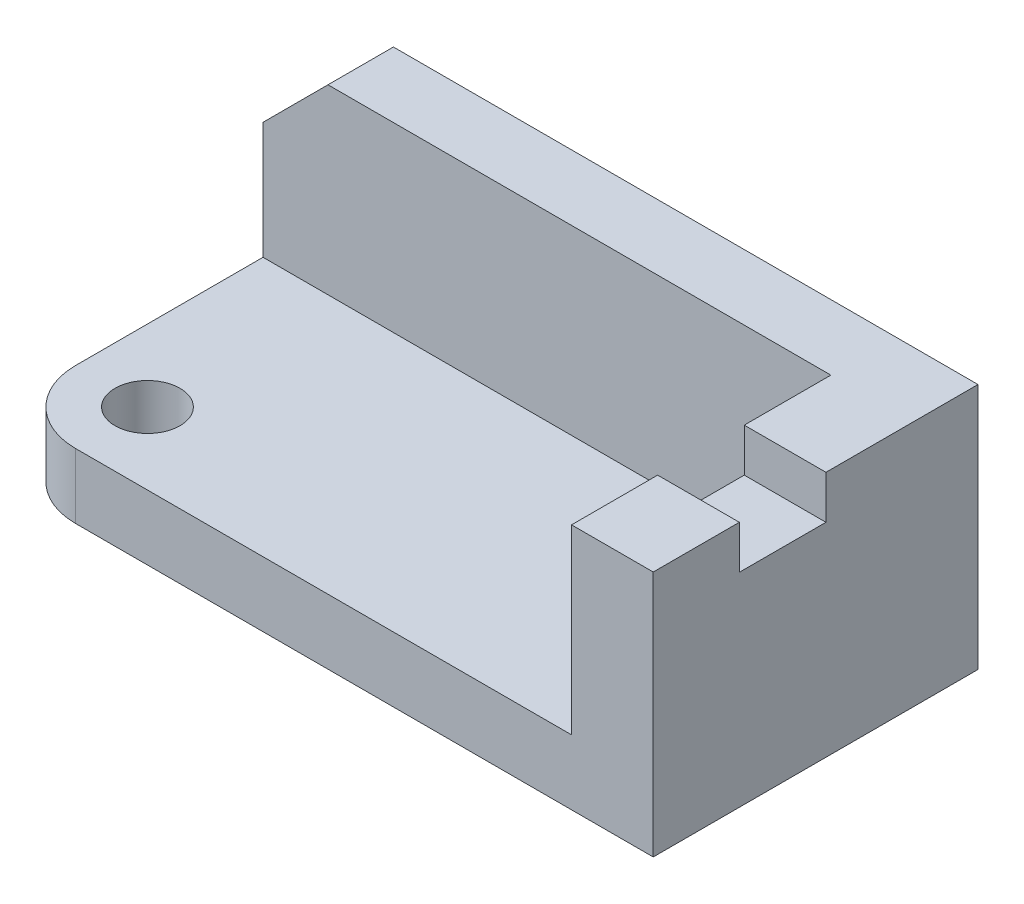
SolidWorks part; units mm, degrees
ref_plane "Front Plane" through (0, 0, 0) normal (0, 0, 1) x (1, 0, 0)
ref_plane "Top Plane" through (0, 0, 0) normal (0, 1, 0) x (1, 0, 0)
ref_plane "Right Plane" through (0, 0, 0) normal (1, 0, 0) x (0, 0, -1)
sketch "Sketch1" plane through (0, 0, 0) normal (0, 1, 0) x (1, 0, 0)
  line L1 (-133.3966, -75) -> (0, -75)
  line L2 (-150, -58.3966) -> (-150, 0)
  line L3 (-150, 0) -> (0, 0)
  line L4 (0, -75) -> (0, 0)
  arc A0 (-150, -58.3966) -> (-133.3966, -75) centre (-133.3966, -58.3966) ccw
  circle A1 centre (-133.3966, -58.3966) radius 7.5
  point P4 (0, 0)
  point P7 (0, 0)
  point P9 (0, 0)
  point P11 (-133.3966, -61.9037)
  dimension "D3" = 150
  dimension "D1" = 15
  dimension "D4" = 16.6034
  dimension "D2" = 75
extrude "Boss-Extrude1" add sketch "Sketch1" along normal blind 15
ref_plane "Plane1" through (0, 15, 75) normal (0, 0, -1) x (-1, 0, 0)
sketch "Sketch3" plane through (0, 15, 0) normal (0, 1, 0) x (1, 0, 0)
  line L0 (-150, 0) -> (-150, -58.3966) construction
  line L1 (0, 0) -> (-150, 0)
  line L2 (0, 0) -> (0, -15.1133)
  line L3 (-18.8648, -15.1133) -> (-150, -15.1133)
  line L4 (-150, 0) -> (-150, -15.1133)
  line L5 (20.625, -75) -> (-20.625, -75) construction
  line L7 (-18.8648, -15.1133) -> (-18.8648, -75)
  line L8 (-18.8648, -75) -> (0, -75)
  line L9 (0, -15.1133) -> (0, -75)
  line L10 (0, -75) -> (0, 0) construction
extrude "Boss-Extrude2" add sketch "Sketch3" along normal blind 42
chamfer "Chamfer2" distance 15 angle 45 1 edges at (-150, 57, 7.5567)
sketch "Sketch4" plane through (0, 57, 0) normal (0, 1, 0) x (1, 0, 0)
  line L0 (-18.8648, -15.1133) -> (-18.8648, -75) construction
  line L1 (-18.8648, -35.1133) -> (0, -35.1133)
  line L2 (-18.8648, -35.1133) -> (-18.8648, -55.1133)
  line L3 (-18.8648, -55.1133) -> (0, -55.1133)
  line L4 (0, -35.1133) -> (0, -55.1133)
  line L5 (0, -75) -> (0, 0) construction
  line L6 (-135, -15.1133) -> (-18.8648, -15.1133) construction
  dimension "D1" = 20
  dimension "D2" = 20
extrude "Cut-Extrude2" cut sketch "Sketch4" against normal blind 10
